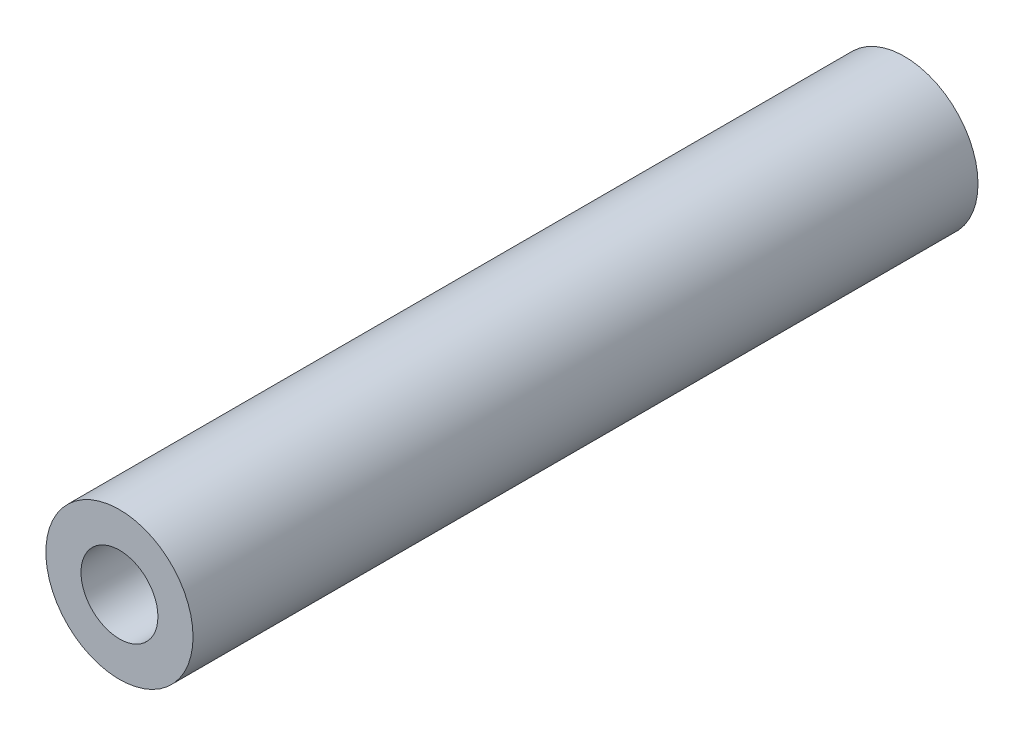
SolidWorks part; units mm, degrees
ref_plane "Front Plane" through (0, 0, 0) normal (0, 0, 1) x (1, 0, 0)
ref_plane "Top Plane" through (0, 0, 0) normal (0, 1, 0) x (1, 0, 0)
ref_plane "Right Plane" through (0, 0, 0) normal (1, 0, 0) x (0, 0, -1)
sketch "Sketch1" plane through (0, 0, 0) normal (0, 0, 1) x (1, 0, 0)
  circle A0 centre (0, 0) radius 2.4892
  circle A1 centre (0, 0) radius 4.7625
  dimension "D1" = 4.9784
  dimension "D2" = 9.525
extrude "Boss-Extrude1" add sketch "Sketch1" along normal mid plane 50.8
